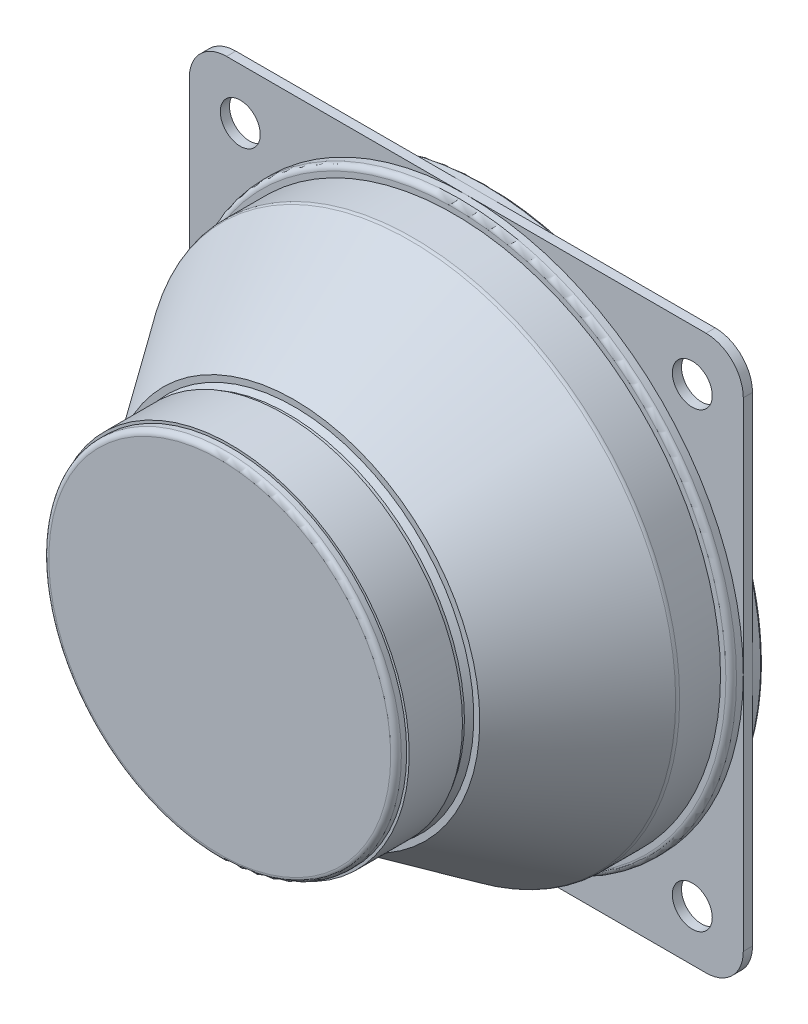
SolidWorks part; units mm, degrees
material "6063-T6"
ref_plane "Front Plane" through (0, 0, 0) normal (0, 0, 1) x (1, 0, 0)
ref_plane "Top Plane" through (0, 0, 0) normal (0, 1, 0) x (1, 0, 0)
ref_plane "Right Plane" through (0, 0, 0) normal (1, 0, 0) x (0, 0, -1)
sketch "Sketch1" plane through (0, 0, 0) normal (0, 0, 1) x (1, 0, 0)
  line L0 (135.0281, 271.9399) -> (799.6948, 271.9399) construction
  line L1 (22.5, -26) -> (-22.5, -26)
  line L2 (26, -22.5) -> (26, 22.5)
  line L3 (22.5, 26) -> (-22.5, 26)
  line L4 (-26, -22.5) -> (-26, 22.5)
  line L5 (26, -26) -> (-26, 26) construction
  line L6 (26, 26) -> (-26, -26) construction
  line L7 (0, 26) -> (0, -26) construction
  line L8 (-26, 0) -> (26, 0) construction
  circle A0 centre (-21.2132, 21.2132) radius 1.875
  circle A1 centre (21.2132, 21.2132) radius 1.875
  circle A2 centre (-21.2132, -21.2132) radius 1.875
  circle A3 centre (21.2132, -21.2132) radius 1.875
  arc A4 (-22.5, 26) -> (-26, 22.5) centre (-22.5, 22.5) ccw
  arc A5 (26, 22.5) -> (22.5, 26) centre (22.5, 22.5) ccw
  arc A6 (22.5, -26) -> (26, -22.5) centre (22.5, -22.5) ccw
  arc A7 (-22.5, -26) -> (-26, -22.5) centre (-22.5, -22.5) cw
  point P0 (0, 0)
  dimension "D3" = 3.75
  dimension "D4" = 60
  dimension "D5" = 3.5
  dimension "D1" = 52
  dimension "D2" = 52
extrude "Boss-Extrude1" add sketch "Sketch1" along normal blind 0.8636
sketch "Sketch4" plane through (0, 0, 0) normal (1, 0, 0) x (0, 0, -1)
  line L0 (0, 0) -> (-69.5136, 0) construction
  line L1 (0.475, 0) -> (-0.475, 0) construction
  line L2 (-0.8636, -26) -> (0, -26) construction
  line L3 (-0.8636, -26) -> (0, -26)
  line L4 (-0.8636, -26) -> (-2, -26)
  line L5 (-2, -26) -> (-2, -25)
  line L6 (-2, -25) -> (-5.9936, -25)
  line L7 (-5.9936, -25) -> (-17, -17.4019)
  line L8 (-17, -17.4019) -> (-17, -16.8424)
  line L9 (-17, -16.8424) -> (-17.5849, -16.4386)
  line L10 (-17.5849, -16.4386) -> (-17.5849, -16.5481)
  line L11 (-17.5849, -16.5481) -> (-18, -16.5481)
  line L12 (-18, -16.5481) -> (-18, -16.7814)
  line L13 (-18, -16.7814) -> (-23, -16.7814)
  line L14 (-23, -16.7814) -> (-23, -16.5455)
  line L15 (-23, -16.5455) -> (-24, -16.5455)
  line L16 (-24, -16.5455) -> (-24, 0)
  line L17 (-0.8636, -26) -> (-0.8636, 0)
  line L18 (0, 171.325) -> (0, -171.325) construction
  line L19 (-0.8636, 0) -> (-24, 0)
  point P0 (0, 0)
  dimension "D1" = 2
  dimension "D2" = 24
  dimension "D3" = 1
  dimension "D4" = 5
  dimension "D5" = 1
  dimension "D6" = 1
revolve "Revolve1" add sketch "Sketch4" angle 360 about L0
sketch "Sketch5" plane through (0, 0, 0) normal (0, 0, -1) x (-1, 0, 0)
  circle A0 centre (0, 0) radius 26
  dimension "D1" = 52
sketch "Sketch6" plane through (0, 0, 0) normal (0, 1, 0) x (1, 0, 0)
  line L6 (-26, 0) -> (-24.8966, 0)
  line L7 (-26, 0) -> (-26, 0.7733)
  line L8 (-25.85, 0.9233) -> (-24.8966, 0.9233)
  line L9 (-24.8966, 0) -> (-24.8966, 0.9233)
  arc A1 (-26, 0.7733) -> (-25.85, 0.9233) centre (-25.85, 0.7733) cw
  dimension "D1" = 0.15
sweep "Sweep2" add profiles "Sketch6" path "Sketch5"
sketch "Sketch7" plane through (0, 0, 0) normal (0, 1, 0) x (1, 0, 0)
  line L0 (-24.8966, 0) -> (-24.8966, 0.9233) construction
  line L1 (-24.8966, 0) -> (-24.8966, 0.9233)
  line L2 (0, 0.9233) -> (0, -24) construction
  line L3 (24.8966, 0.9233) -> (-24.8966, 0.9233) construction
  line L4 (-16.5455, -24) -> (16.5455, -24) construction
  line L5 (0, -5.9936) -> (0, 0.9233)
  line L6 (-25, -5.9936) -> (25, -5.9936) construction
  line L7 (0, 0.9233) -> (-24.8966, 0.9233)
  arc A0 (-24.8966, 0) -> (-19.9536, -2.246) centre (-23.1627, -2.7464) cw
  arc A1 (-19.9536, -2.246) -> (0, -5.9936) centre (0, 48.9998) ccw
revolve "Cut-Revolve1" cut sketch "Sketch7" angle 360 about L2
sketch "Sketch8" plane through (0, 0, 0) normal (0, 1, 0) x (1, 0, 0)
  line L0 (-19.9536, -2.246) -> (-24.8966, 0)
  arc A0 (-19.9536, -2.246) -> (-24.8966, 0) centre (-23.1627, -2.7464) ccw construction
  arc A1 (-19.9536, -2.246) -> (-24.8966, 0) centre (-23.1627, -2.7464) ccw
revolve "Revolve2" add sketch "Sketch8" angle 360 about L5
fillet "Fillet1" radius 0.5 3 edges at (-16.5455, 0, 24) (-25, 0, 5.9936) (-26, 0, 2)
